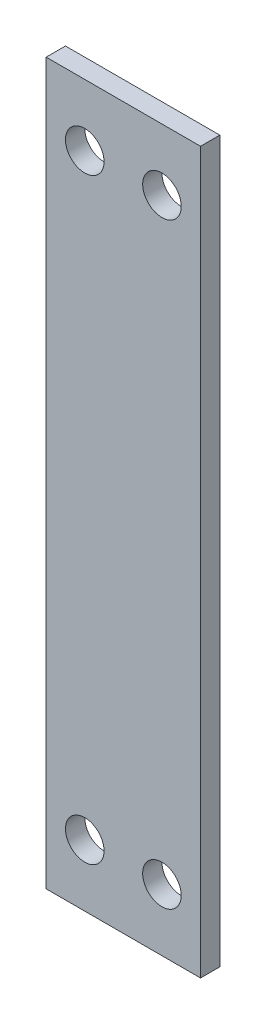
SolidWorks part; units mm, degrees
ref_plane "Front Plane" through (0, 0, 0) normal (0, 0, 1) x (1, 0, 0)
ref_plane "Top Plane" through (0, 0, 0) normal (0, 1, 0) x (1, 0, 0)
ref_plane "Right Plane" through (0, 0, 0) normal (1, 0, 0) x (0, 0, -1)
sketch "Sketch1" plane through (0, 0, 0) normal (0, 0, 1) x (1, 0, 0)
  line L0 (0, 9.9974) -> (38.1, 9.9974) construction
  line L1 (0, 0) -> (38.1, 0)
  line L2 (0, 0) -> (0, 177.8)
  line L3 (0, 177.8) -> (38.1, 177.8)
  line L4 (38.1, 0) -> (38.1, 177.8)
  line L5 (19.05, 15.24) -> (38.1, 15.24) construction
  line L6 (19.05, 225.3621) -> (38.1, 225.3621) construction
  circle A0 centre (9.525, 15.24) radius 4.7625
  circle A1 centre (28.575, 15.24) radius 4.7625
  circle A2 centre (9.525, 162.56) radius 4.7625
  circle A3 centre (28.575, 162.56) radius 4.7625
  point P13 (19.05, 9.9974)
  point P14 (28.575, 15.24)
  point P21 (19.05, 177.8)
  point P22 (28.575, 225.3621)
  dimension "D4" = 9.525
  dimension "D6" = 9.525
  dimension "10" = 177.8
  dimension "D2" = 38.1
  dimension "D3" = 19.05
  dimension "D5" = 162.56
  dimension "D7" = 19.05
  dimension "D8" = 15.24
extrude "Boss-Extrude1" add sketch "Sketch1" along normal blind 4.7625
